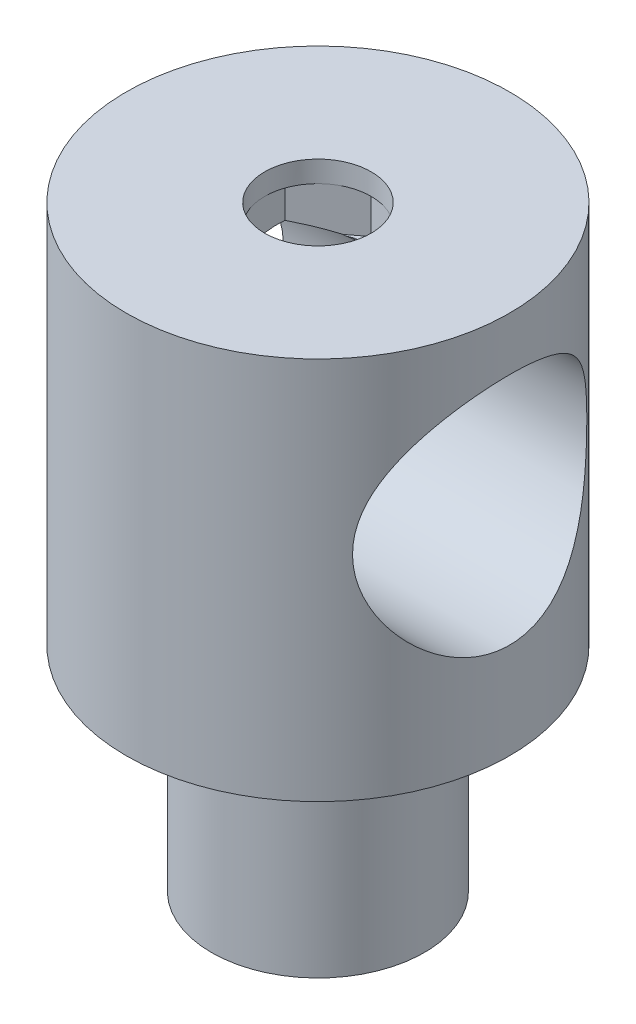
SolidWorks part; units mm, degrees
ref_plane "Front Plane" through (0, 0, 0) normal (0, 0, 1) x (1, 0, 0)
ref_plane "Top Plane" through (0, 0, 0) normal (0, 1, 0) x (1, 0, 0)
ref_plane "Right Plane" through (0, 0, 0) normal (1, 0, 0) x (0, 0, -1)
sketch "Sketch1" plane through (0, 0, 0) normal (0, 1, 0) x (1, 0, 0)
  circle A0 centre (0, 0) radius 9
  dimension "D1" = 18
extrude "Boss-Extrude1" add sketch "Sketch1" along normal blind 18
sketch "Sketch2" plane through (0, 18, 0) normal (0, 1, 0) x (1, 0, 0)
  circle A0 centre (0, 0) radius 2.5
  dimension "D1" = 5
sketch "Sketch4" plane through (0, 0, 0) normal (1, 0, 0) x (0, 0, -1)
  circle A0 centre (0, 10) radius 5.5
  dimension "D1" = 11
  dimension "D2" = 10
extrude "Cut-Extrude1" cut sketch "Sketch4" against normal through all both and the other way through all
extrude "Cut-Extrude2" cut sketch "Sketch2" against normal blind 5
sketch "Sketch7" plane through (0, 18, 0) normal (0, 1, 0) x (1, 0, 0)
  line L1 (-2.2991, -1.7457) -> (0.3622, -2.8639)
  line L2 (0.3622, -2.8639) -> (2.6614, -1.1183)
  line L3 (2.6614, -1.1183) -> (2.2991, 1.7457)
  line L4 (2.2991, 1.7457) -> (-0.3622, 2.8639)
  line L5 (-0.3622, 2.8639) -> (-2.6614, 1.1183)
  line L6 (-2.6614, 1.1183) -> (-2.2991, -1.7457)
  circle A0 centre (0, 0) radius 2.5 construction
  dimension "D1" = 5
extrude "Cut-Extrude6" cut sketch "Sketch7" against normal blind 2 from offset 1 offset against normal yes
sketch "Sketch8" plane through (0, 0, 0) normal (0, -1, 0) x (1, 0, 0)
  circle A0 centre (0, 0) radius 5
  dimension "D1" = 10
extrude "Boss-Extrude2" add sketch "Sketch8" along normal blind 10
